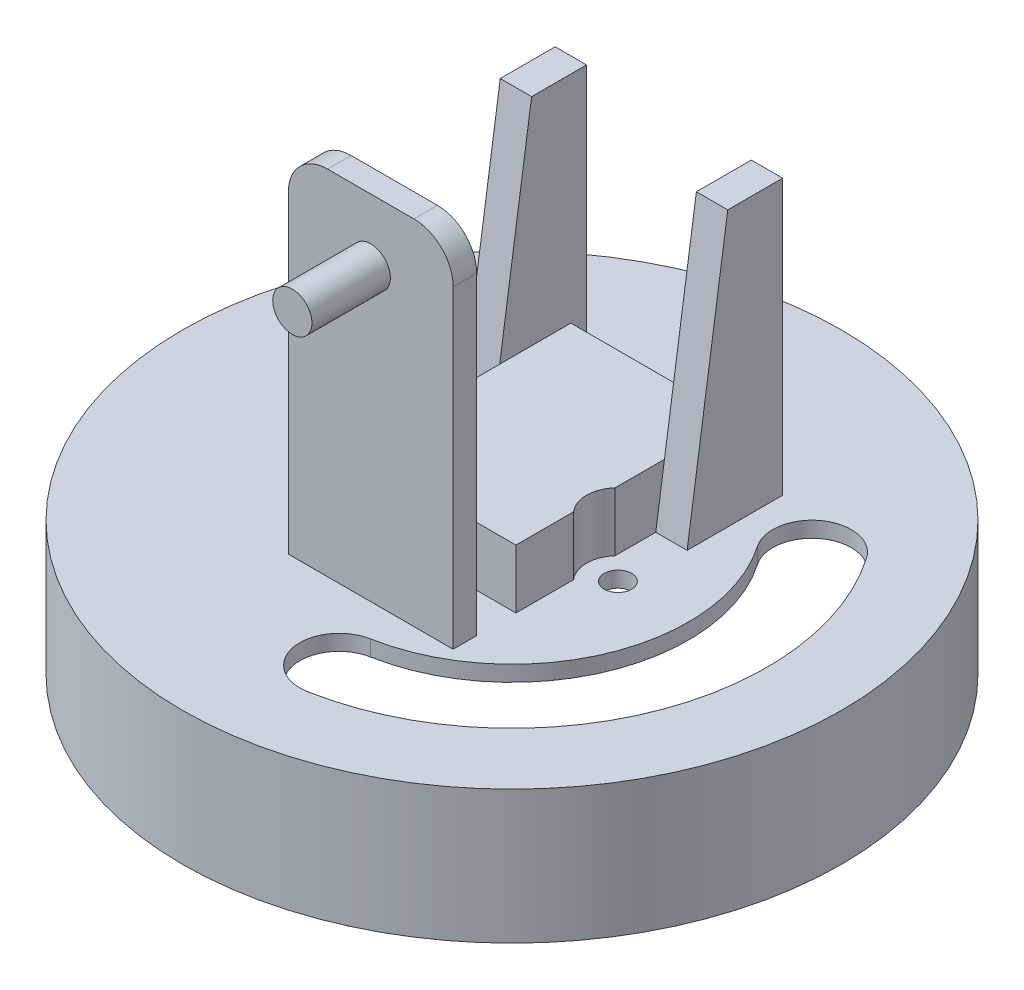
SolidWorks part; units mm, degrees
ref_plane "Ön Düzlem" through (0, 0, 0) normal (0, 0, 1) x (1, 0, 0)
ref_plane "Üst Düzlem" through (0, 0, 0) normal (0, 1, 0) x (1, 0, 0)
ref_plane "Sağ Düzlem" through (0, 0, 0) normal (1, 0, 0) x (0, 0, -1)
sketch "Çizim1" plane through (0, 0, 0) normal (0, 1, 0) x (1, 0, 0)
  circle A0 centre (0, 0) radius 42
  circle A1 centre (0, 0) radius 40
extrude "Yükseklik-Ekstrüzyon1" add sketch "Çizim1" along normal blind 15
sketch "Çizim2" plane through (0, 15, 0) normal (0, 1, 0) x (1, 0, 0)
  circle A0 centre (0, 0) radius 42
extrude "Yükseklik-Ekstrüzyon2" add sketch "Çizim2" along normal blind 2
sketch "Çizim3" plane through (0, 17, 0) normal (0, 1, 0) x (1, 0, 0)
  circle A0 centre (-13.5, 0) radius 1.75
  circle A1 centre (13.5, 0) radius 1.75
extrude "Kes-Ekstrüzyon1" cut sketch "Çizim3" against normal blind 2
sketch "Çizim4" plane through (0, 17, 0) normal (0, 1, 0) x (1, 0, 0)
  line L0 (0, -27.0416) -> (0, -27.0416)
  line L1 (19.1213, 19.1213) -> (19.1213, 19.1213)
  arc A0 (4.0909, -22.125) -> (18.5374, 12.752) centre (0, 0) ccw
  arc A1 (5.9091, -31.9583) -> (26.7763, 18.4196) centre (0, 0) ccw
  arc A2 (0, -27.0416) -> (5.9091, -31.9583) centre (5, -27.0416) ccw
  arc A3 (0, -27.0416) -> (4.0909, -22.125) centre (5, -27.0416) cw
  arc A4 (19.1213, 19.1213) -> (26.7763, 18.4196) centre (22.6569, 15.5858) cw
  arc A5 (19.1213, 19.1213) -> (18.5374, 12.752) centre (22.6569, 15.5858) ccw
  point P8 (0, -32.5)
  point P11 (0, -22.5)
  dimension "D1" = 5
extrude "Kes-Ekstrüzyon2" cut sketch "Çizim4" against normal blind 2 contours A4 A5 A0 A3 A2 A1
sketch "Çizim5" plane through (0, 17, 0) normal (0, 1, 0) x (1, 0, 0)
  line L0 (-10.5, -10) -> (-10.5, -2.6458)
  line L2 (10.5, 18) -> (10.5, 2.6458)
  line L3 (-10.5, -10) -> (10.5, -10)
  line L4 (10.5, -2.6458) -> (10.5, -10)
  line L5 (-10.5, 18) -> (10.5, 18)
  line L6 (-10.5, 2.6458) -> (-10.5, 18)
  arc A0 (-10.5, -2.6458) -> (-10.5, 2.6458) centre (-13.5, 0) ccw
  arc A1 (10.5, 2.6458) -> (10.5, -2.6458) centre (13.5, 0) ccw
extrude "Yükseklik-Ekstrüzyon3" add sketch "Çizim5" along normal blind 7.5
sketch "Çizim6" plane through (0, 17, 0) normal (0, 1, 0) x (1, 0, 0)
  line L0 (-10.5, 18) -> (-10.5, 13)
  line L1 (-10.5, 18) -> (-10.5, 2.6458) construction
  line L2 (-10.5, 13) -> (-14.5, 13)
  line L3 (-14.5, 13) -> (-14.5, 20)
  line L4 (-14.5, 20) -> (-10.5, 20)
  line L5 (-10.5, 20) -> (-10.5, 18)
  line L8 (10.5, 20) -> (10.5, 18)
  line L9 (14.5, 20) -> (10.5, 20)
  line L10 (14.5, 13) -> (14.5, 20)
  line L11 (10.5, 13) -> (14.5, 13)
  line L12 (10.5, 18) -> (10.5, 13)
  dimension "D1" = 7
extrude "Yükseklik-Ekstrüzyon4" add sketch "Çizim6" along normal blind 35
sketch "Çizim7" plane through (10.5, 0, 0) normal (1, 0, 0) x (0, 0, -1)
  line L0 (13, 52) -> (7.8229, 17)
  line L1 (2.6458, 17) -> (13, 17) construction
  line L2 (7.8229, 17) -> (13, 17)
  line L3 (13, 17) -> (13, 52)
extrude "Yükseklik-Ekstrüzyon5" add sketch "Çizim7" along normal blind 4
sketch "Çizim8" plane through (-10.5, 0, 0) normal (-1, 0, 0) x (0, 0, 1)
  line L0 (-13, 52) -> (-7.8229, 17)
  line L1 (-13, 17) -> (-2.6458, 17) construction
  line L2 (-7.8229, 17) -> (-13, 17)
  line L3 (-13, 17) -> (-13, 52)
extrude "Yükseklik-Ekstrüzyon6" add sketch "Çizim8" along normal blind 4
sketch "Çizim9" plane through (0, 17, 0) normal (0, 1, 0) x (1, 0, 0)
  line L1 (10.5, -18) -> (-10.5, -18)
  line L3 (10.5, -15) -> (10.5, -18)
  line L4 (-10.5, -18) -> (-10.5, -15)
  line L5 (-10.5, -15) -> (10.5, -15)
extrude "Yükseklik-Ekstrüzyon7" add sketch "Çizim9" along normal blind 45
sketch "Çizim10" plane through (0, 0, 18) normal (0, 0, 1) x (1, 0, 0)
  circle A0 centre (0, 54) radius 2.5
extrude "Yükseklik-Ekstrüzyon8" add sketch "Çizim10" along normal blind 10
fillet "Radyus1" radius 5 2 edges at (10.5, 62, 16.5) (-10.5, 62, 16.5)
